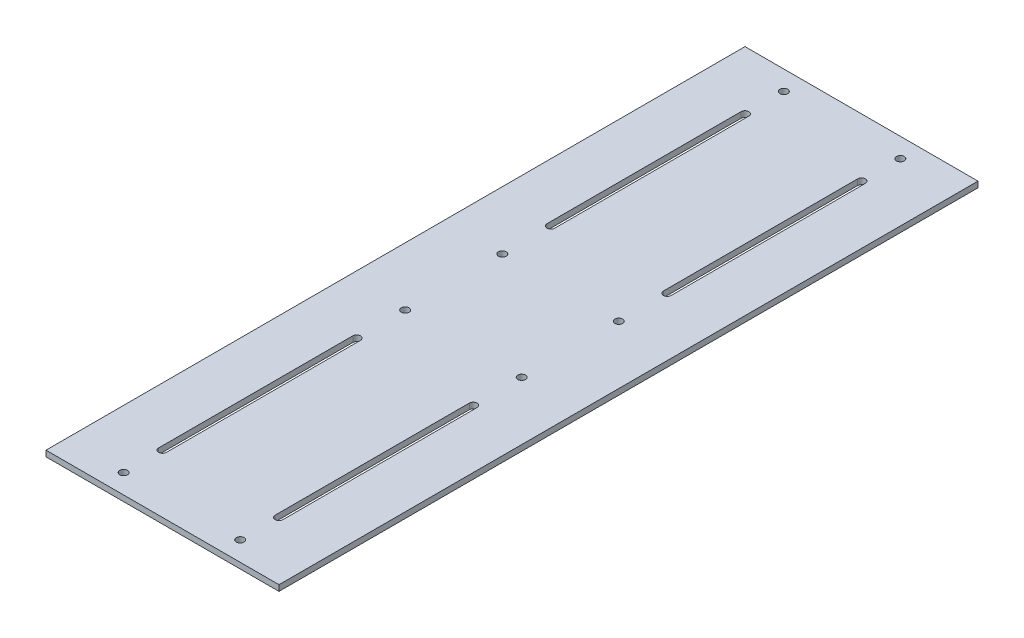
SolidWorks part; units mm, degrees
ref_plane "Front Plane" through (0, 0, 0) normal (0, 0, 1) x (1, 0, 0)
ref_plane "Top Plane" through (0, 0, 0) normal (0, 1, 0) x (1, 0, 0)
ref_plane "Right Plane" through (0, 0, 0) normal (1, 0, 0) x (0, 0, -1)
sketch "Sketch1" plane through (0, 0, 0) normal (0, 1, 0) x (1, 0, 0)
  line L1 (-60, -180) -> (60, -180)
  line L2 (-60, -180) -> (-60, 180)
  line L3 (-60, 180) -> (60, 180)
  line L4 (60, -180) -> (60, 180)
  line L5 (-60, -180) -> (60, 180) construction
  line L6 (-60, 180) -> (60, -180) construction
  point P0 (0, 0)
extrude "Boss-Extrude1" add sketch "Sketch1" along normal blind 3
sketch "Sketch2" plane through (0, 3, 0) normal (0, 1, 0) x (1, 0, 0)
  circle A0 centre (-30, 170) radius 2
  circle A1 centre (30, 170) radius 2
  circle A3 centre (-30, -170) radius 2
  circle A4 centre (30, -170) radius 2
  circle A5 centre (-30, 25) radius 2
  circle A6 centre (30, 25) radius 2
  circle A7 centre (-30, -25) radius 2
  circle A8 centre (30, -25) radius 2
extrude "Cut-Extrude2" cut sketch "Sketch2" against normal through all
sketch "Sketch3" plane through (0, 3, 0) normal (0, 1, 0) x (1, 0, 0)
  line L0 (30, 150) -> (30, 50) construction
  line L1 (32, 150) -> (32, 50)
  line L2 (28, 150) -> (28, 50)
  line L3 (-30, 150) -> (-30, 50) construction
  line L4 (-28, 150) -> (-28, 50)
  line L5 (-32, 150) -> (-32, 50)
  line L6 (30, -150) -> (30, -50) construction
  line L7 (28, -150) -> (28, -50)
  line L8 (32, -150) -> (32, -50)
  line L9 (-30, -150) -> (-30, -50) construction
  line L10 (-32, -150) -> (-32, -50)
  line L11 (-28, -150) -> (-28, -50)
  arc A1 (32, 150) -> (28, 150) centre (30, 150) ccw
  arc A2 (28, 50) -> (32, 50) centre (30, 50) ccw
  arc A3 (-28, 150) -> (-32, 150) centre (-30, 150) ccw
  arc A4 (-32, 50) -> (-28, 50) centre (-30, 50) ccw
  arc A5 (28, -150) -> (32, -150) centre (30, -150) ccw
  arc A6 (32, -50) -> (28, -50) centre (30, -50) ccw
  arc A7 (-32, -150) -> (-28, -150) centre (-30, -150) ccw
  arc A8 (-28, -50) -> (-32, -50) centre (-30, -50) ccw
  point P0 (30, 100)
  point P7 (-30, 100)
  point P16 (30, -100)
  point P23 (-30, -100)
extrude "Cut-Extrude3" cut sketch "Sketch3" against normal through all
